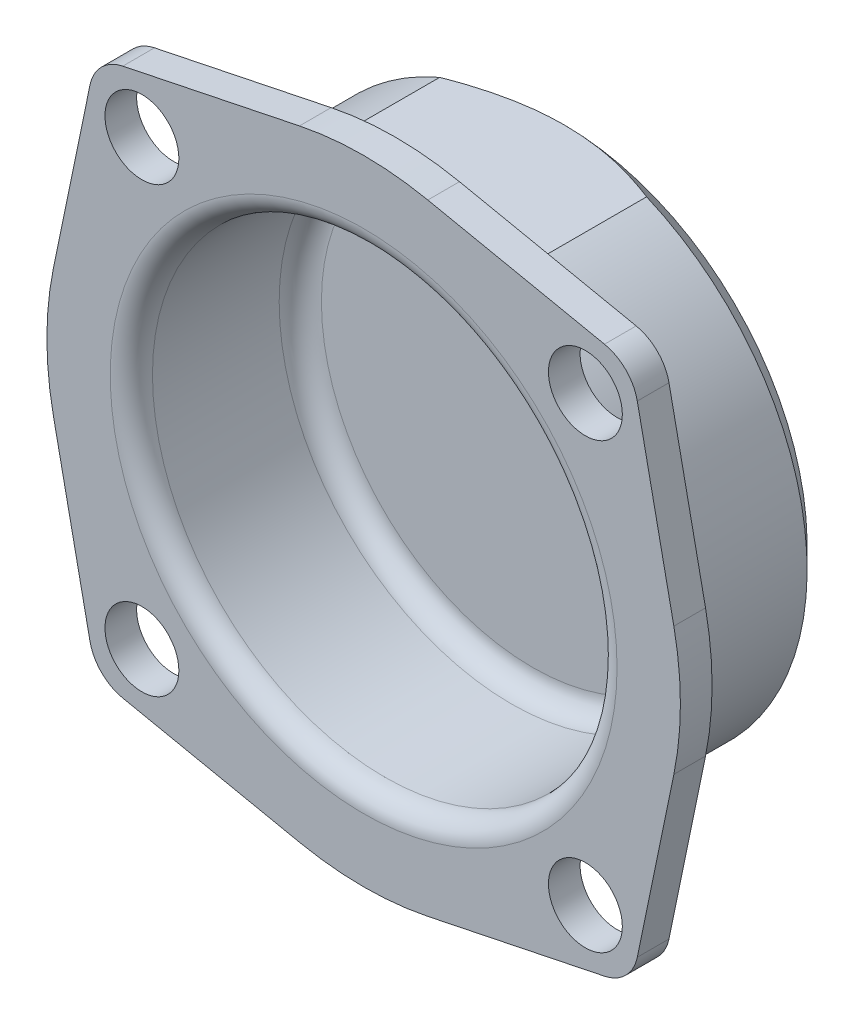
SolidWorks part; units mm, degrees
ref_plane "Face" through (0, 0, 0) normal (0, 0, 1) x (1, 0, 0)
ref_plane "Dessus" through (0, 0, 0) normal (0, 1, 0) x (1, 0, 0)
ref_plane "Droite" through (0, 0, 0) normal (1, 0, 0) x (0, 0, -1)
sketch "Esquisse1" plane through (0, 0, 0) normal (0, 0, 1) x (1, 0, 0)
  line L0 (-11.4051, -12.9585) -> (-3.0382, -14.6891)
  line L1 (-10.5, 10.5) -> (10.5, 10.5) construction
  line L2 (-10.5, 10.5) -> (-10.5, -10.5) construction
  line L5 (3.0382, -14.6891) -> (11.4051, -12.9585)
  line L6 (12.9585, -11.4051) -> (14.6891, -3.0382)
  line L7 (14.6891, 3.0382) -> (12.9585, 11.4051)
  line L8 (11.4051, 12.9585) -> (3.0382, 14.6891)
  line L9 (-11.4051, 12.9585) -> (-3.0382, 14.6891)
  line L10 (-12.9585, 11.4051) -> (-14.6891, 3.0382)
  line L11 (-14.6891, -3.0382) -> (-12.9585, -11.4051)
  arc A0 (14.6891, -3.0382) -> (14.6891, 3.0382) centre (0, 0) ccw
  circle A1 centre (-10.5, 10.5) radius 1.75
  arc A2 (11.4051, -12.9585) -> (12.9585, -11.4051) centre (11, -11) ccw
  arc A3 (12.9585, 11.4051) -> (11.4051, 12.9585) centre (11, 11) ccw
  arc A4 (-11.4051, 12.9585) -> (-12.9585, 11.4051) centre (-11, 11) ccw
  arc A5 (-12.9585, -11.4051) -> (-11.4051, -12.9585) centre (-11, -11) ccw
  circle A6 centre (10.5, 10.5) radius 1.75
  circle A7 centre (-10.5, -10.5) radius 1.75
  circle A8 centre (10.5, -10.5) radius 1.75
  arc A9 (3.0382, 14.6891) -> (-3.0382, 14.6891) centre (0, 0) ccw
  arc A10 (-14.6891, 3.0382) -> (-14.6891, -3.0382) centre (0, 0) ccw
  arc A17 (-3.0382, -14.6891) -> (3.0382, -14.6891) centre (0, 0) ccw
  dimension "D1" = 30
  dimension "D2" = 10.5
  dimension "D7" = 4
  dimension "D4" = 3.5
  dimension "D3" = 10.5
  dimension "D5" = 22
  dimension "D6" = 22
  dimension "D8" = 11
  dimension "D9" = 22
  dimension "D10" = 11
  dimension "D11" = 90
extrude "Base-Extrusion" add sketch "Esquisse1" along normal blind 1.5
sketch "Esquisse2" plane through (0, 0, 0) normal (0, 0, -1) x (-1, 0, 0)
  circle A0 centre (0, 0) radius 12.5
  dimension "D1" = 25
extrude "Boss.-Extru.1" add sketch "Esquisse2" along normal blind 8
chamfer "Chanfrein1" distance 1 angle 45 1 edges at (-12.5, 0, -8)
sketch "Esquisse3" plane through (0, 0, 1.5) normal (0, 0, 1) x (1, 0, 0)
  circle A0 centre (0, 0) radius 11
  dimension "D1" = 22
extrude "Enlèv. mat.-Extru.1" cut sketch "Esquisse3" against normal blind 8
fillet "Congé1" radius 1 2 edges at (11, 0, -6.5) (11, 0, 1.5)
sketch "Esquisse4" plane through (0, 0, 0) normal (0, 0, -1) x (-1, 0, 0)
  line L1 (-7.6799, 17.0815) -> (7.4636, 17.0815)
  line L2 (-7.6799, 17.0815) -> (-7.6799, 11.5)
  line L3 (-7.6799, 11.5) -> (7.4636, 11.5)
  line L4 (7.4636, 17.0815) -> (7.4636, 11.5)
  dimension "D1" = 11.5
extrude "Enlèv. mat.-Extru.3" cut sketch "Esquisse4" along normal blind 8
sketch "Esquisse5" plane through (0, 0, 1.5) normal (0, 0, 1) x (1, 0, 0)
  line L1 (0, 0) -> (-20.0347, 0)
  line L2 (0, 0) -> (0, 17.6198)
  line L3 (0, 17.6198) -> (-20.0347, 17.6198)
  line L4 (-20.0347, 0) -> (-20.0347, 17.6198)
extrude "Enlèv. mat.-Extru.4" [suppressed] cut sketch "Esquisse5" against normal through all
